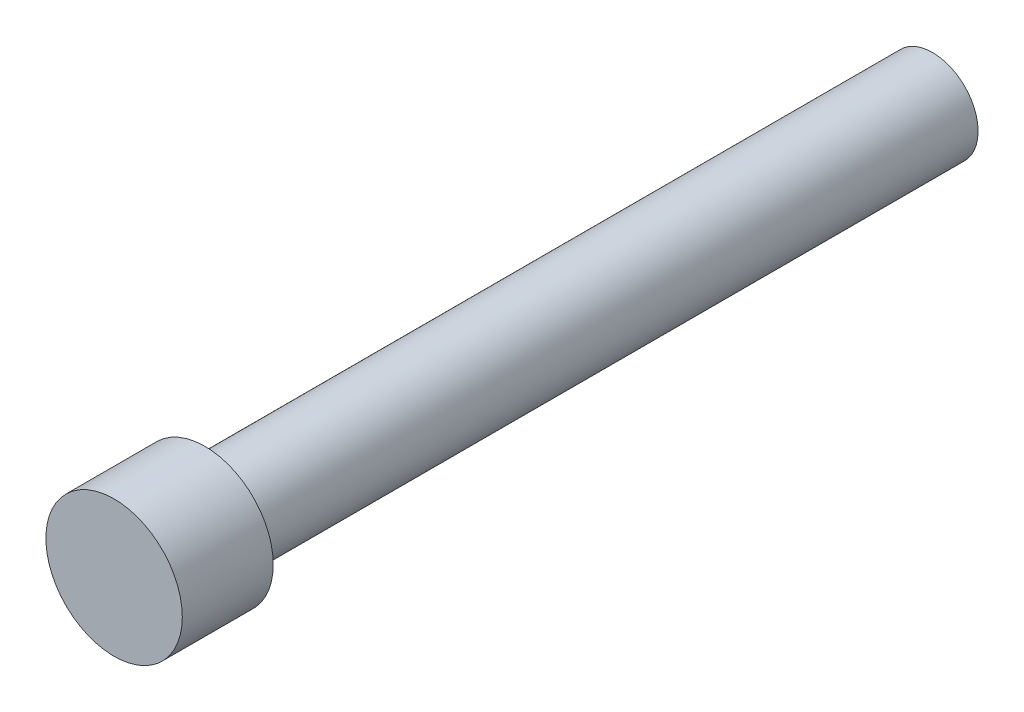
SolidWorks part; units mm, degrees
ref_plane "前视基准面" through (0, 0, 0) normal (0, 0, 1) x (1, 0, 0)
ref_plane "上视基准面" through (0, 0, 0) normal (0, 1, 0) x (1, 0, 0)
ref_plane "右视基准面" through (0, 0, 0) normal (1, 0, 0) x (0, 0, -1)
sketch "草图1" plane through (0, 0, 0) normal (0, 0, 1) x (1, 0, 0)
  circle A0 centre (0, 0) radius 1.5
  dimension "D1" = 3
extrude "凸台-拉伸1" add sketch "草图1" along normal blind 2
sketch "草图2" plane through (0, 0, 0) normal (0, 0, -1) x (-1, 0, 0)
  circle A0 centre (0, 0) radius 1
  dimension "D1" = 2
extrude "凸台-拉伸3" add sketch "草图2" along normal blind 16
